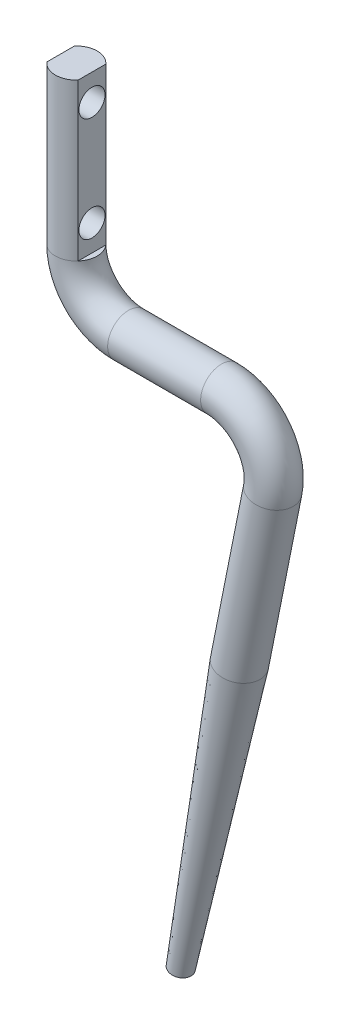
SolidWorks part; units mm, degrees
material "AISI 304"
ref_plane "前视基准面" through (0, 0, 0) normal (0, 0, 1) x (1, 0, 0)
ref_plane "上视基准面" through (0, 0, 0) normal (0, 1, 0) x (1, 0, 0)
ref_plane "右视基准面" through (0, 0, 0) normal (1, 0, 0) x (0, 0, -1)
sketch "Sketch1" plane through (0, 0, 0) normal (0, 0, 1) x (1, 0, 0)
  line L0 (0, 40) -> (0, 10)
  line L1 (10, 0) -> (27.802, 0)
  line L2 (37.6078, -11.9612) -> (20, -100)
  arc A0 (27.802, 0) -> (37.6078, -11.9612) centre (27.802, -10) cw
  arc A1 (0, 10) -> (10, 0) centre (10, 10) ccw
  point P7 (40, 0)
  point P10 (0, 0)
  dimension "D5" = 10
  dimension "D1" = 40
  dimension "D2" = 40
  dimension "D3" = 100
  dimension "D4" = 20
ref_plane "Plane1" through (0, 40, 0) normal (0, 1, 0) x (1, 0, 0)
sketch "Sketch3" plane through (0, 40, 0) normal (0, 1, 0) x (1, 0, 0)
  circle A0 centre (0, 0) radius 4
  dimension "D1" = 8
sweep "Sweep1" add profiles "Sketch3" path "Sketch1"
chamfer "Chamfer1" distance 2 angle 88 1 edges at (20, -100, 4)
sketch "Sketch4" plane through (0, 40, 0) normal (0, 1, 0) x (1, 0, 0)
  line L1 (3, 17.7651) -> (-3, 17.7651)
  line L2 (3, 17.7651) -> (3, -17.7651)
  line L3 (3, -17.7651) -> (-3, -17.7651)
  line L4 (-3, 17.7651) -> (-3, -17.7651)
  line L5 (3, 17.7651) -> (-3, -17.7651) construction
  line L6 (3, -17.7651) -> (-3, 17.7651) construction
  point P0 (0, 0)
  point P5 (0, 0)
  dimension "D1" = 3
extrude "Extrude1" cut sketch "Sketch4" against normal blind 30 flip side to cut
hole_wizard "M6 Tapped Hole1" positions "Sketch5" profile "Sketch6" tap size "M6" standard "GB"
sketch "Sketch5" plane through (3, 0, 0) normal (1, 0, 0) x (0, 0, -1)
  line L0 (-2.6458, 10) -> (2.6458, 10) construction
  point P0 (0, 35)
  point P2 (0, 15)
  dimension "D1" = 20
  dimension "D2" = 5
sketch "Sketch6" plane through (3, 35, 0) normal (0, 1, 0) x (0, 0, -1)
  line L0 (0, 0) -> (0, 10.5022)
  line L1 (0, 10.5022) -> (2.5, 9)
  line L2 (2.5, 9) -> (2.5, 0)
  line L5 (2.5, 0) -> (0, 0)
  line L10 (0, 10.5022) -> (-2.5, 9) construction
  line L11 (0, -6.35) -> (0, 107.95) construction
  dimension "螺纹孔钻头直径" = 5
  dimension "螺纹孔钻头深度" = 9
  dimension "导头角度" = 118
